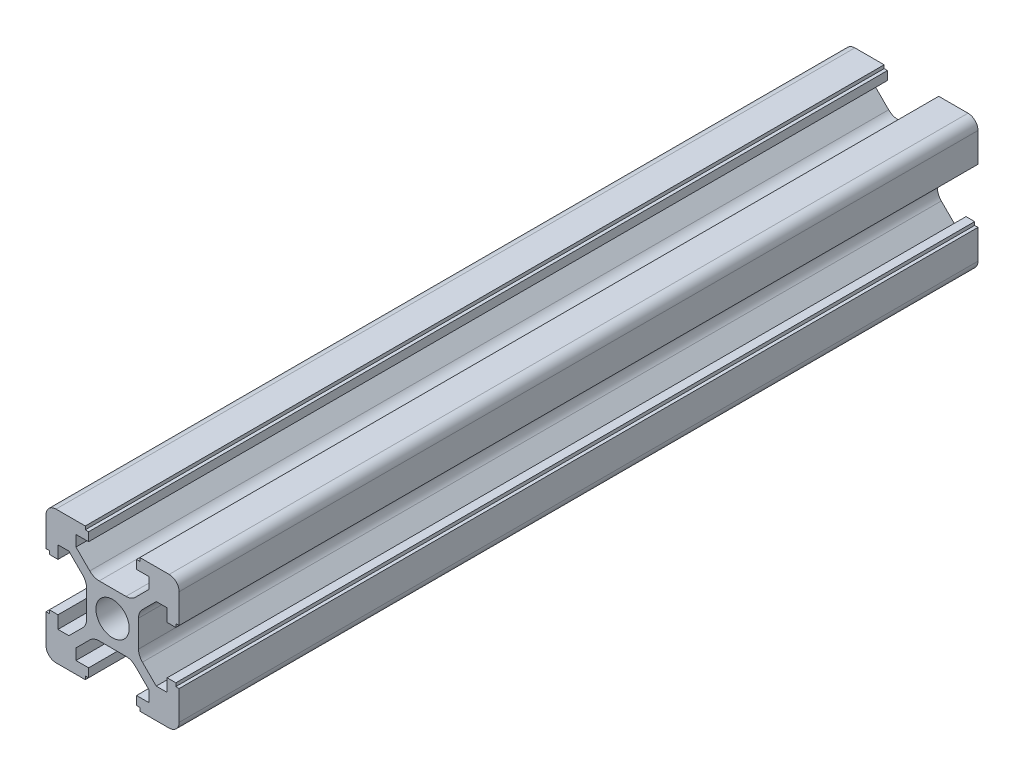
SolidWorks part; units mm, degrees
material "6063-O"
ref_plane "Front Plane" through (0, 0, 0) normal (0, 0, 1) x (1, 0, 0)
ref_plane "Top Plane" through (0, 0, 0) normal (0, 1, 0) x (1, 0, 0)
ref_plane "Right Plane" through (0, 0, 0) normal (1, 0, 0) x (0, 0, -1)
sketch "Sketch1" plane through (0, 0, 0) normal (0, 0, 1) x (1, 0, 0)
  line L0 (10, -4.1) -> (10, -8.5)
  line L1 (4.1, 10) -> (8.5, 10)
  line L2 (8.5, -10) -> (4.1, -10)
  line L3 (-8.5, -10) -> (-4.1, -10)
  line L4 (10, 8.5) -> (10, 4.1)
  line L7 (8.5, 10) -> (4.1, 10)
  line L8 (5.5, 6.5607) -> (3.4251, 4.4858)
  line L9 (8.5, 10) -> (4.1, 10)
  line L10 (3.9, 2.0109) -> (3.9, -2.0109)
  line L11 (2.0109, -3.9) -> (-2.0109, -3.9)
  line L12 (-3.9, -2.0109) -> (-3.9, 2.0109)
  line L13 (-2.0109, 3.9) -> (2.8393, 3.9)
  line L14 (2.5, 0) -> (22.2403, 0) construction
  line L15 (3.6, 9.5) -> (3.6, 8.2)
  line L16 (9.5, 3.6) -> (8.2, 3.6)
  line L17 (8.2, 3.6) -> (8.2, 5.5)
  line L18 (8.2, 5.5) -> (6.5607, 5.5)
  line L19 (10, -4.1) -> (10, -8.5)
  line L20 (4.1, 9.5) -> (3.6, 9.5)
  line L21 (4.1, 10) -> (4.1, 9.5)
  line L22 (8.5, 10) -> (4.1, 10)
  line L23 (10, 4.1) -> (9.5, 4.1)
  line L24 (9.5, 4.1) -> (9.5, 3.6)
  line L25 (5.5, 8.2) -> (5.5, 6.5607)
  line L26 (3.6, 8.2) -> (5.5, 8.2)
  line L27 (4.4858, 3.4251) -> (6.5607, 5.5)
  line L28 (10, -8.5) -> (10, -4.1)
  line L29 (6.5607, -5.5) -> (4.4858, -3.4251)
  line L30 (10, -8.5) -> (10, -4.1)
  line L31 (2.0109, -3.9) -> (-2.0109, -3.9)
  line L32 (3.9, 2.8393) -> (3.9, -2.0109)
  line L33 (9.5, -3.6) -> (8.2, -3.6)
  line L34 (3.6, -9.5) -> (3.6, -8.2)
  line L35 (3.6, -8.2) -> (5.5, -8.2)
  line L36 (5.5, -8.2) -> (5.5, -6.5607)
  line L37 (9.5, -4.1) -> (9.5, -3.6)
  line L38 (10, -4.1) -> (9.5, -4.1)
  line L39 (10, -8.5) -> (10, -4.1)
  line L40 (4.1, -10) -> (4.1, -9.5)
  line L41 (4.1, -9.5) -> (3.6, -9.5)
  line L42 (8.2, -5.5) -> (6.5607, -5.5)
  line L43 (8.2, -3.6) -> (8.2, -5.5)
  line L44 (3.4251, -4.4858) -> (5.5, -6.5607)
  line L45 (-4.1, -10) -> (-8.5, -10)
  line L46 (-10, -8.5) -> (-10, -4.1)
  line L47 (-8.5, -10) -> (-4.1, -10)
  line L48 (-5.5, -6.5607) -> (-3.4251, -4.4858)
  line L49 (-8.5, -10) -> (-4.1, -10)
  line L50 (-3.9, -2.0109) -> (-3.9, 2.0109)
  line L51 (2.0109, -3.9) -> (-2.0109, -3.9)
  line L52 (-3.6, -9.5) -> (-3.6, -8.2)
  line L53 (-9.5, -3.6) -> (-8.2, -3.6)
  line L54 (-8.2, -3.6) -> (-8.2, -5.5)
  line L55 (-8.2, -5.5) -> (-6.5607, -5.5)
  line L56 (-4.1, -9.5) -> (-3.6, -9.5)
  line L57 (-4.1, -10) -> (-4.1, -9.5)
  line L58 (-8.5, -10) -> (-4.1, -10)
  line L59 (-10, -4.1) -> (-9.5, -4.1)
  line L60 (-9.5, -4.1) -> (-9.5, -3.6)
  line L61 (-5.5, -8.2) -> (-5.5, -6.5607)
  line L62 (-3.6, -8.2) -> (-5.5, -8.2)
  line L63 (-4.4858, -3.4251) -> (-6.5607, -5.5)
  line L64 (-10, 4.1) -> (-10, 8.5)
  line L65 (-8.5, 10) -> (-4.1, 10)
  line L66 (-10, 8.5) -> (-10, 4.1)
  line L67 (-6.5607, 5.5) -> (-4.4858, 3.4251)
  line L68 (-10, 8.5) -> (-10, 4.1)
  line L69 (-2.0109, 3.9) -> (2.0109, 3.9)
  line L70 (-3.9, -2.0109) -> (-3.9, 2.0109)
  line L71 (-9.5, 3.6) -> (-8.2, 3.6)
  line L72 (-3.6, 9.5) -> (-3.6, 8.2)
  line L73 (-3.6, 8.2) -> (-5.5, 8.2)
  line L74 (-5.5, 8.2) -> (-5.5, 6.5607)
  line L75 (-9.5, 4.1) -> (-9.5, 3.6)
  line L76 (-10, 4.1) -> (-9.5, 4.1)
  line L77 (-10, 8.5) -> (-10, 4.1)
  line L78 (-4.1, 10) -> (-4.1, 9.5)
  line L79 (-4.1, 9.5) -> (-3.6, 9.5)
  line L80 (-8.2, 5.5) -> (-6.5607, 5.5)
  line L81 (-8.2, 3.6) -> (-8.2, 5.5)
  line L82 (-3.4251, 4.4858) -> (-5.5, 6.5607)
  line L83 (4.1, -10) -> (8.5, -10)
  arc A0 (2.0109, -3.9) -> (3.4251, -4.4858) centre (2.0109, -5.9) cw
  arc A1 (4.4858, -3.4251) -> (3.9, -2.0109) centre (5.9, -2.0109) cw
  arc A2 (3.9, 2.0109) -> (4.4858, 3.4251) centre (5.9, 2.0109) cw
  arc A3 (2.0109, 3.9) -> (3.4251, 4.4858) centre (2.0109, 5.9) ccw
  arc A4 (-2.0109, 3.9) -> (-3.4251, 4.4858) centre (-2.0109, 5.9) cw
  arc A5 (-4.4858, 3.4251) -> (-3.9, 2.0109) centre (-5.9, 2.0109) cw
  arc A6 (-3.4251, -4.4858) -> (-2.0109, -3.9) centre (-2.0109, -5.9) cw
  arc A7 (-3.9, -2.0109) -> (-4.4858, -3.4251) centre (-5.9, -2.0109) cw
  circle A8 centre (0, 0) radius 2.5
  arc A9 (-8.5, -10) -> (-10, -8.5) centre (-8.5, -8.5) cw
  arc A10 (-10, 8.5) -> (-8.5, 10) centre (-8.5, 8.5) cw
  arc A11 (8.5, 10) -> (10, 8.5) centre (8.5, 8.5) cw
  arc A12 (8.5, -10) -> (10, -8.5) centre (8.5, -8.5) ccw
  point P0 (0, 0)
  point P86 (0, 0)
  point P107 (10, -10)
  dimension "D3" = 2
  dimension "D5" = 5
  dimension "D2" = 1.5
  dimension "D8" = 1.5
  dimension "D6" = 4
  dimension "D7" = 6.1
  dimension "D11" = 0.5
  dimension "D12" = 0.5
extrude "Boss-Extrude2" add sketch "Sketch1" along normal blind 120
ref_plane "平面1" through (-8.5, 10, 120) normal (0, 0, -1) x (-1, 0, 0)
